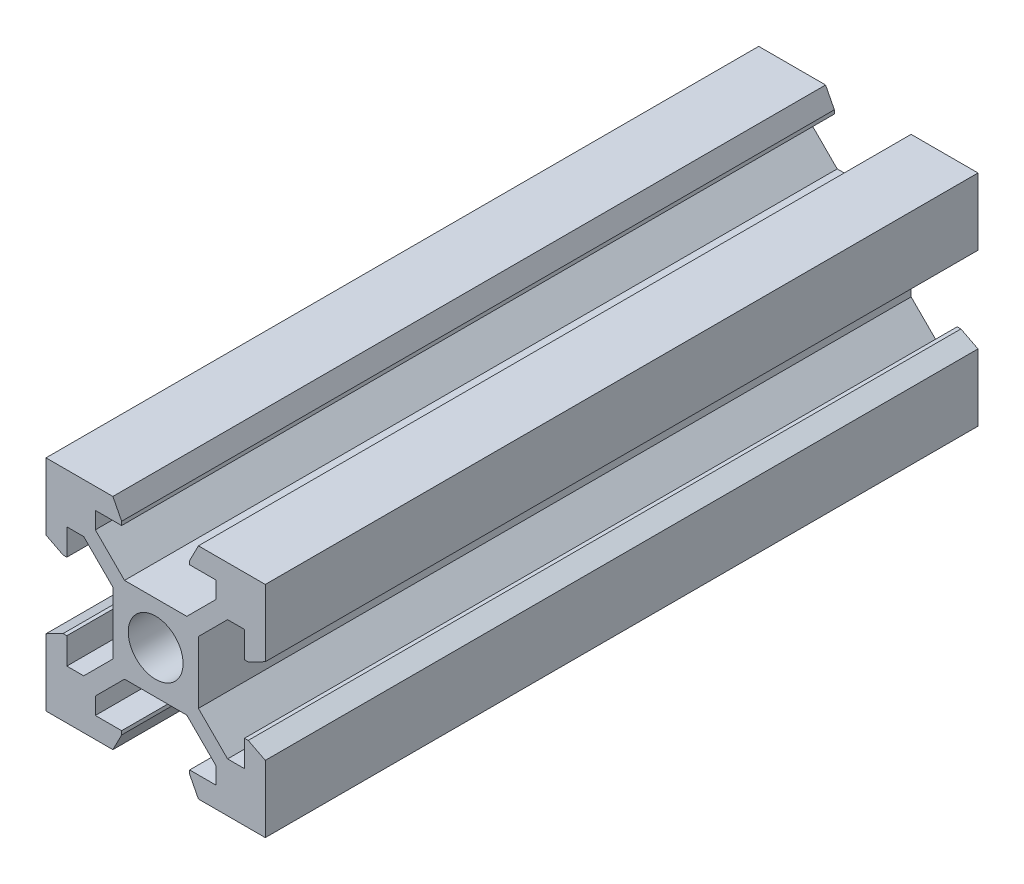
SolidWorks part; units mm, degrees
ref_plane "Front Plane" through (0, 0, 0) normal (0, 0, 1) x (1, 0, 0)
ref_plane "Top Plane" through (0, 0, 0) normal (0, 1, 0) x (1, 0, 0)
ref_plane "Right Plane" through (0, 0, 0) normal (1, 0, 0) x (0, 0, -1)
sketch "Sketch1" plane through (0, 0, 0) normal (0, 0, 1) x (1, 0, 0)
  line L0 (0, 20) -> (0, 13.8958)
  line L1 (0, 0) -> (20, 0)
  line L2 (0, 0) -> (0, 20)
  line L3 (0, 20) -> (20, 20)
  line L4 (20, 0) -> (20, 20)
  line L5 (0, 13.8958) -> (1.56, 13.1)
  line L6 (1.56, 13.1) -> (1.9, 13.1)
  line L7 (1.9, 13.1) -> (1.9, 15.5)
  line L8 (1.9, 15.5) -> (3.4393, 15.5)
  line L9 (3.4393, 15.5) -> (6.2656, 12.6737)
  line L10 (6.2656, 12.6737) -> (7.3263, 13.7344)
  line L11 (7.3263, 13.7344) -> (4.5, 16.5607)
  line L12 (4.5, 16.5607) -> (4.5, 18.1)
  line L13 (4.5, 18.1) -> (6.9, 18.1)
  line L14 (6.9, 18.1) -> (6.9, 18.44)
  line L15 (6.9, 18.44) -> (6.1, 20)
  line L16 (6.1, 20) -> (0, 20)
  line L17 (10, 10) -> (6.1, 13.9)
  line L18 (6.1, 6.1) -> (13.9, 6.1)
  line L19 (6.1, 6.1) -> (6.1, 13.9)
  line L20 (6.1, 13.9) -> (13.9, 13.9)
  line L21 (13.9, 6.1) -> (13.9, 13.9)
  line L22 (6.796, 13.204) -> (4.0494, 15.9506)
  line L23 (10, 10) -> (10, 24.9145) construction
  line L24 (13.1, 18.44) -> (13.9, 20)
  line L25 (13.1, 18.1) -> (13.1, 18.44)
  line L26 (15.5, 18.1) -> (13.1, 18.1)
  line L27 (15.5, 16.5607) -> (15.5, 18.1)
  line L28 (12.6737, 13.7344) -> (15.5, 16.5607)
  line L29 (13.7344, 12.6737) -> (12.6737, 13.7344)
  line L30 (16.5607, 15.5) -> (13.7344, 12.6737)
  line L31 (18.1, 15.5) -> (16.5607, 15.5)
  line L32 (18.1, 13.1) -> (18.1, 15.5)
  line L33 (18.44, 13.1) -> (18.1, 13.1)
  line L34 (20, 13.8958) -> (18.44, 13.1)
  line L35 (10, 10) -> (22.1718, 10)
  line L36 (20, 6.1042) -> (18.44, 6.9)
  line L37 (18.44, 6.9) -> (18.1, 6.9)
  line L38 (18.1, 6.9) -> (18.1, 4.5)
  line L39 (18.1, 4.5) -> (16.5607, 4.5)
  line L40 (16.5607, 4.5) -> (13.7344, 7.3263)
  line L41 (13.7344, 7.3263) -> (12.6737, 6.2656)
  line L42 (12.6737, 6.2656) -> (15.5, 3.4393)
  line L43 (15.5, 3.4393) -> (15.5, 1.9)
  line L44 (15.5, 1.9) -> (13.1, 1.9)
  line L45 (13.1, 1.9) -> (13.1, 1.56)
  line L46 (13.1, 1.56) -> (13.9, 0)
  line L47 (6.9, 1.56) -> (6.1, 0)
  line L48 (6.9, 1.9) -> (6.9, 1.56)
  line L49 (4.5, 1.9) -> (6.9, 1.9)
  line L50 (4.5, 3.4393) -> (4.5, 1.9)
  line L51 (7.3263, 6.2656) -> (4.5, 3.4393)
  line L52 (6.2656, 7.3263) -> (7.3263, 6.2656)
  line L53 (3.4393, 4.5) -> (6.2656, 7.3263)
  line L54 (1.9, 4.5) -> (3.4393, 4.5)
  line L55 (1.9, 6.9) -> (1.9, 4.5)
  line L56 (1.56, 6.9) -> (1.9, 6.9)
  line L57 (0, 6.1042) -> (1.56, 6.9)
  circle A0 centre (10, 10) radius 2.5
  point P21 (2.6697, 15.5)
  dimension "D3" = 5
  dimension "D1" = 20
  dimension "D2" = 20
  dimension "D4" = 10
  dimension "D5" = 10
  dimension "D6" = 7.8
  dimension "D7" = 7.8
  dimension "D8" = 6.1
  dimension "D9" = 6.1
  dimension "D10" = 6.9
  dimension "D11" = 6.9
  dimension "D12" = 6.1042
  dimension "D13" = 6.1
  dimension "D14" = 0.34
  dimension "D15" = 0.34
  dimension "D16" = 1.9
  dimension "D17" = 4.5
  dimension "D18" = 4.5
  dimension "D19" = 1.5
  dimension "D20" = 1.9
extrude "Boss-Extrude1" add sketch "Sketch1" along normal blind 65
